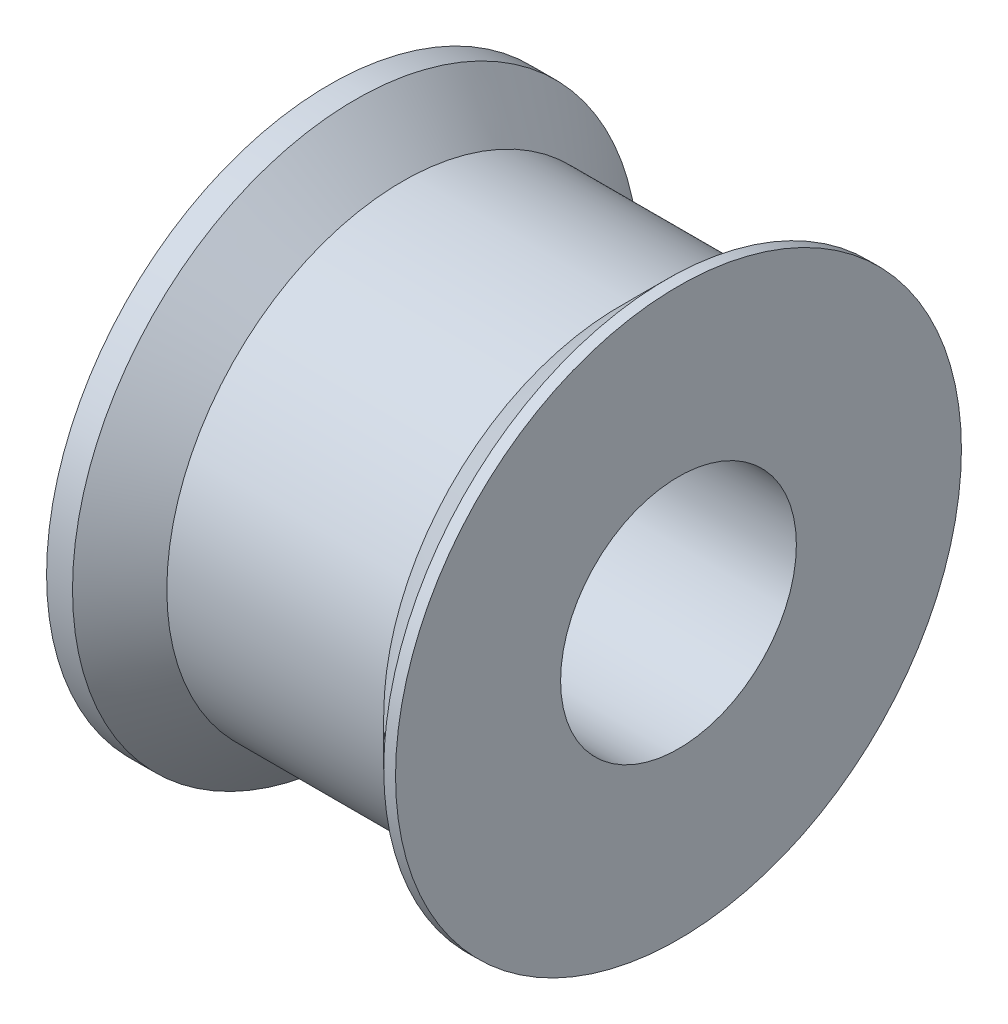
SolidWorks part; units mm, degrees
ref_plane "Front Plane" through (0, 0, 0) normal (0, 0, 1) x (1, 0, 0)
ref_plane "Top Plane" through (0, 0, 0) normal (0, 1, 0) x (1, 0, 0)
ref_plane "Right Plane" through (0, 0, 0) normal (1, 0, 0) x (0, 0, -1)
sketch "Sketch2" plane through (0, 0, 0) normal (0, 1, 0) x (1, 0, 0)
  line L0 (-7.1, 12) -> (-6.6, 12)
  line L1 (-6.6, 12) -> (-4.6, 10)
  line L2 (-4.6, 10) -> (4.6, 10)
  line L3 (4.6, 10) -> (6.6, 12)
  line L4 (6.6, 12) -> (7.1, 12)
  line L5 (7.1, 12) -> (7.1, 0)
  line L6 (-7.1, 12) -> (-7.1, 0) construction
  line L7 (-54.6936, 0) -> (47.2254, 0) construction
  line L8 (0, -23.2469) -> (0, 34.557) construction
  line L9 (7.1, 0) -> (-7.1, 0)
  line L10 (-7.1, 12) -> (-7.7, 12)
  line L11 (-7.7, 12) -> (-7.7, 0)
  line L12 (-7.7, 0) -> (-7.1, 0)
  line L13 (-7.1, 0) -> (-7.7, 0)
  point P16 (0, 10)
  dimension "D1" = 12
  dimension "D2" = 2.5
  dimension "D3" = 9.2
  dimension "D4" = 10
  dimension "D5" = 0.6
revolve "Revolve1" add sketch "Sketch2" angle 360 about L9
sketch "Sketch3" plane through (-7.7, 0, 0) normal (-1, 0, 0) x (0, 0, 1)
  circle A0 centre (0, 0) radius 2
  dimension "D1" = 4
extrude "Cut-Extrude1" cut sketch "Sketch3" against normal up to surface (14.8 mm away) up to face at (7.1, 0, -12)
sketch "Sketch4" plane through (-7.7, 0, 0) normal (-1, 0, 0) x (0, 0, 1)
  circle A0 centre (0, 0) radius 5
  dimension "D1" = 10
extrude "Cut-Extrude2" cut sketch "Sketch4" against normal up to surface (12.8 mm away) from offset 2 up to face at (7.1, 0, 2) offset against normal yes
